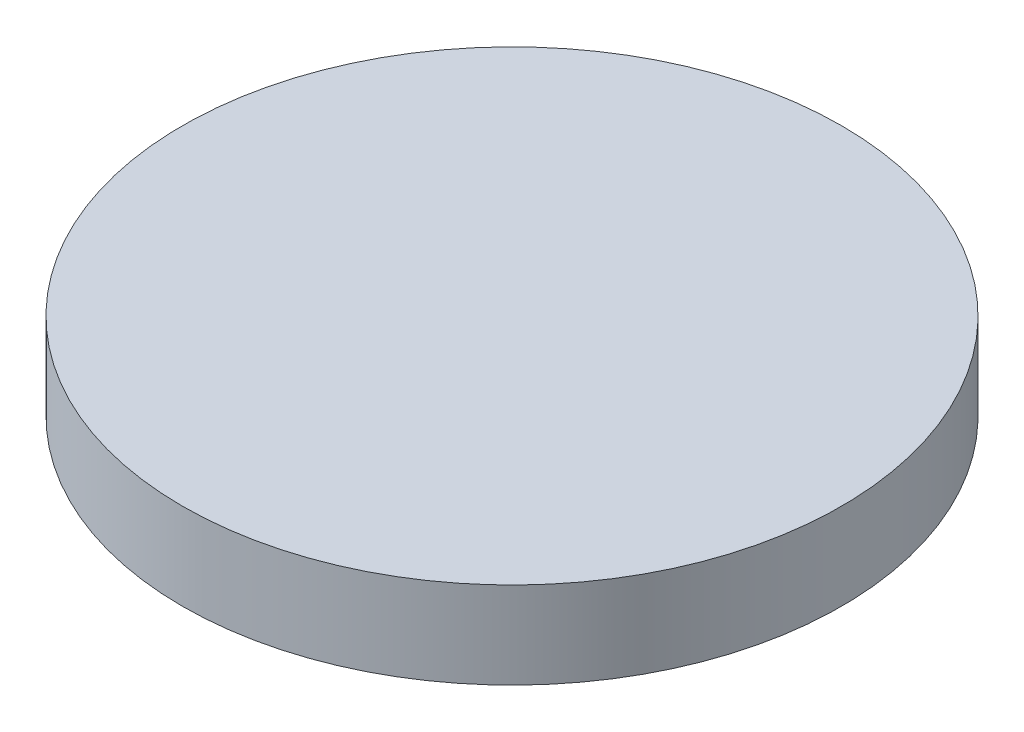
SolidWorks part; units mm, degrees
ref_plane "Front Plane" through (0, 0, 0) normal (0, 0, 1) x (1, 0, 0)
ref_plane "Top Plane" through (0, 0, 0) normal (0, 1, 0) x (1, 0, 0)
ref_plane "Right Plane" through (0, 0, 0) normal (1, 0, 0) x (0, 0, -1)
sketch "Sketch1" plane through (0, 0, 0) normal (0, 1, 0) x (1, 0, 0)
  circle A0 centre (4.9997, -4.9619) radius 12.065
  dimension "D1" = 24.13
extrude "Boss-Extrude1" add sketch "Sketch1" along normal blind 3.175
